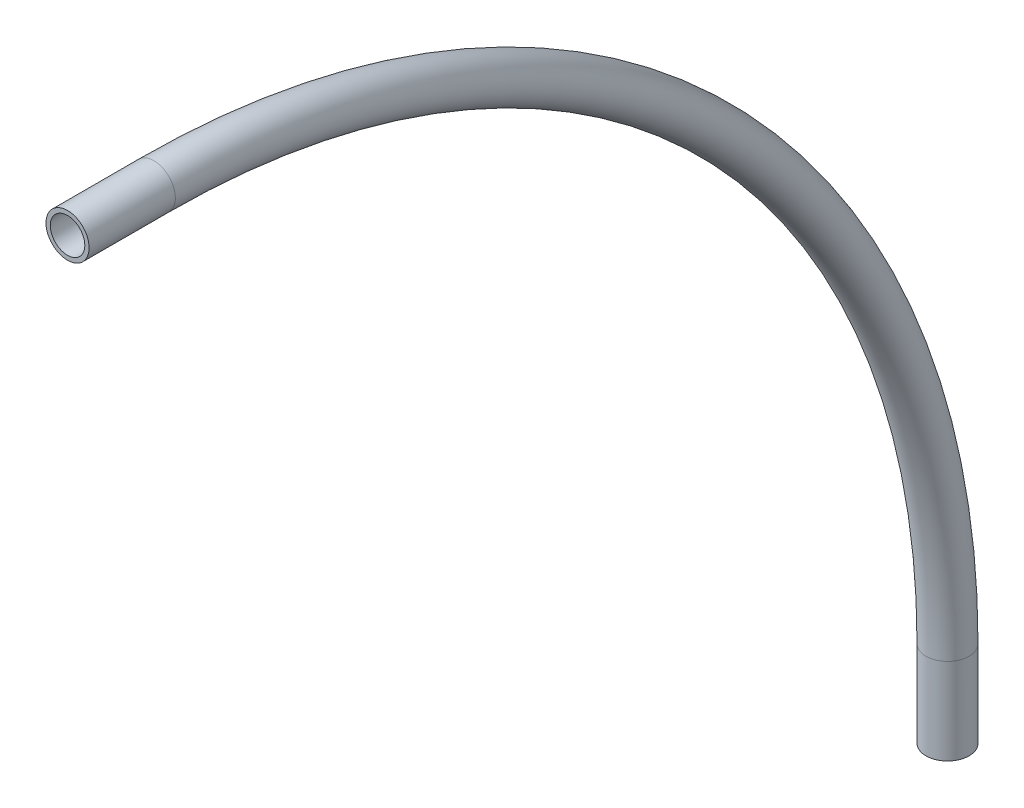
SolidWorks part; units mm, degrees
material "Acrylic (Medium-high impact)"
ref_plane "Front" through (0, 0, 0) normal (0, 0, 1) x (1, 0, 0)
ref_plane "Top" through (0, 0, 0) normal (0, 1, 0) x (1, 0, 0)
ref_plane "Right" through (0, 0, 0) normal (1, 0, 0) x (0, 0, -1)
sketch "Sketch1" plane through (0, 0, 0) normal (0, 0, 1) x (1, 0, 0)
  circle A0 centre (0, 0) radius 2.54
  circle A1 centre (0, 0) radius 3.175
  dimension "D1" = 6.35
  dimension "D2" = 5.08
sketch "Sketch2" plane through (0, 0, 0) normal (1, 0, 0) x (0, 0, -1)
  line L0 (0, 0) -> (12.7, 0)
  line L1 (0, 2.54) -> (0, -2.54) construction
  line L2 (129.54, -116.84) -> (129.54, -129.54)
  arc A0 (12.7, 0) -> (129.54, -116.84) centre (12.7, -116.84) cw
  dimension "D1" = 90
  dimension "D2" = 12.7
  dimension "D3" = 116.84
sweep "Sweep1" add profiles "Sketch1" path "Sketch2"
